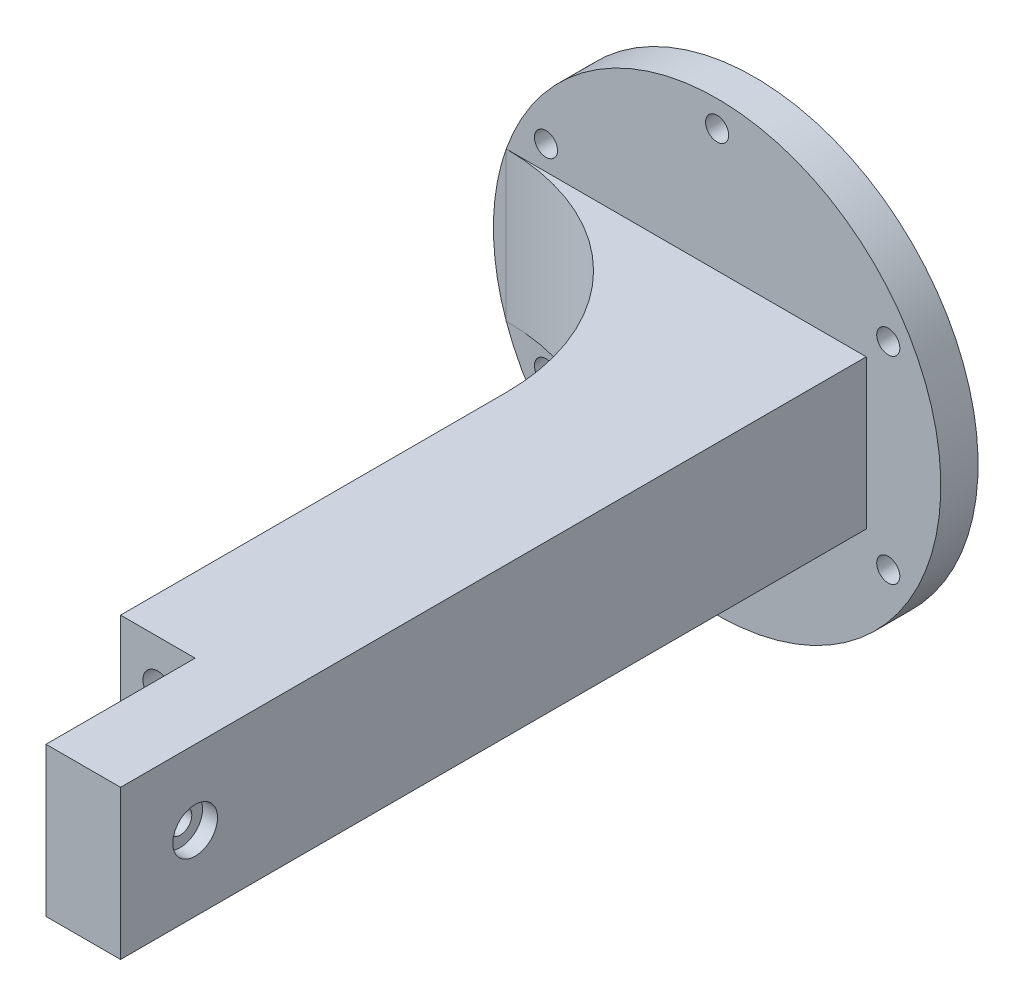
SolidWorks part; units mm, degrees
ref_plane "前视基准面" through (0, 0, 0) normal (0, 0, 1) x (1, 0, 0)
ref_plane "上视基准面" through (0, 0, 0) normal (0, 1, 0) x (1, 0, 0)
ref_plane "右视基准面" through (0, 0, 0) normal (1, 0, 0) x (0, 0, -1)
other "Configuration Table"
sketch "草图1" plane through (0, 0, 0) normal (0, 0, 1) x (1, 0, 0)
  line L1 (-16.3775, 3.1798) -> (3.6225, 3.1798)
  line L2 (-16.3775, 3.1798) -> (-16.3775, -16.8202)
  line L3 (-16.3775, -16.8202) -> (3.6225, -16.8202)
  line L4 (3.6225, 3.1798) -> (3.6225, -16.8202)
extrude "凸台-拉伸1" add sketch "草图1" along normal blind 140 contours L2 L1 L4 L3
sketch "草图2" plane through (0, 0, 0) normal (0, 0, -1) x (-1, 0, 0)
  line L1 (16.3775, 3.1798) -> (16.3775, -16.8202) construction
  circle A0 centre (16.3775, -6.8202) radius 30
  circle A4 centre (-6.5721, 6.4298) radius 1.55
  circle A5 centre (16.3775, 19.6798) radius 1.55
  circle A6 centre (39.3272, 6.4298) radius 1.55
  circle A7 centre (39.3272, -20.0702) radius 1.55
  circle A8 centre (16.3775, -33.3202) radius 1.55
  circle A9 centre (-6.5721, -20.0702) radius 1.55
extrude "凸台-拉伸2" add sketch "草图2" along normal blind 5 contours A4 | A9 | A8 | A7 | A0 | A6 | A5
sketch "草图3" plane through (0, 0, 0) normal (0, 0, 1) x (1, 0, 0)
  line L0 (-16.3775, 3.1798) -> (-44.6618, 3.1798)
  line L1 (-44.6618, 3.1798) -> (-44.6618, -16.8202)
  line L2 (-44.6618, -16.8202) -> (-16.3775, -16.8202)
  line L3 (-16.3775, 3.1798) -> (-16.3775, -16.8202)
  circle A0 centre (-16.3775, -6.8202) radius 30 construction
extrude "凸台-拉伸3" add sketch "草图3" along normal blind 28.2843 contours L3 L2 L1 L0
sketch "草图4" plane through (0, 3.1798, 0) normal (0, 1, 0) x (1, 0, 0)
  line L0 (-44.6618, -28.2843) -> (-44.6618, 0) construction
  line L1 (-44.6618, 0) -> (-44.6618, -28.2843)
  line L2 (-44.6618, -28.2843) -> (-16.3775, -28.2843)
  arc A0 (-16.3775, -28.2843) -> (-44.6618, 0) centre (-44.6618, -28.2843) ccw
extrude "切除-拉伸1" cut sketch "草图4" against normal blind 28.2843 contours L2 A0 L1
sketch "草图6" plane through (0, 3.1798, 0) normal (0, 1, 0) x (1, 0, 0)
  line L0 (3.6225, -140) -> (3.6225, -100)
  line L1 (3.6225, -140) -> (3.6225, 0) construction
  line L3 (-16.3775, -140) -> (-16.3775, -28.2843) construction
  line L4 (-16.3775, -100) -> (-16.3775, -140)
  line L5 (-16.3775, -140) -> (3.6225, -140)
  line L6 (-6.3775, -100) -> (-6.3775, -80)
  line L7 (-6.3775, -80) -> (-16.3775, -80)
  line L8 (-16.3775, -80) -> (-16.3775, -100)
  line L9 (-6.3775, -100) -> (3.6225, -100)
extrude "切除-拉伸2" cut sketch "草图6" against normal blind 28.2843 contours L9 L0 L5 L4 L8 L7 L6
sketch "草图7" plane through (-6.3775, 0, 0) normal (-1, 0, 0) x (0, 0, 1)
  line L0 (80, 3.1798) -> (100, -16.8202)
  line L1 (100, -16.8202) -> (100, 3.1798) construction
  circle A0 centre (90, -6.8202) radius 1.55
extrude "切除-拉伸3" cut sketch "草图7" against normal blind 28.2843 contours L0 A0 | L0 A0
sketch "草图8" plane through (3.6225, 0, 0) normal (1, 0, 0) x (0, 0, -1)
  circle A0 centre (-90, -6.8202) radius 3
extrude "切除-拉伸4" cut sketch "草图8" against normal blind 2 contours A0
sketch "草图9" plane through (0, 0, 80) normal (0, 0, 1) x (1, 0, 0)
  line L0 (-16.3775, 3.1798) -> (-6.3775, -16.8202)
  line L1 (-11.3775, -6.8202) -> (-11.3775, -2.8202)
  circle A0 centre (-11.3775, -2.8202) radius 2
extrude "切除-拉伸5" cut sketch "草图9" against normal blind 100
sketch "草图10" plane through (0, 0, -5) normal (0, 0, -1) x (-1, 0, 0)
  line L3 (16.3775, -4.8202) -> (48.3332, -4.8202)
  line L4 (48.3332, -4.8202) -> (48.3332, -8.8202)
  line L5 (48.3332, -8.8202) -> (16.3775, -8.8202)
  line L7 (11.3775, -2.8202) -> (12.8104, -1.4248)
  line L9 (11.3775, -2.8202) -> (10.2201, -4.4517)
  line L10 (10.2201, -4.4517) -> (16.3775, -8.8202)
  line L11 (12.8104, -1.4248) -> (16.3775, -4.8202)
  circle A1 centre (11.3775, -2.8202) radius 2 construction
extrude "切除-拉伸6" cut sketch "草图10" against normal blind 3 contours L10 L9 L7 L11 L3 L4 L5
